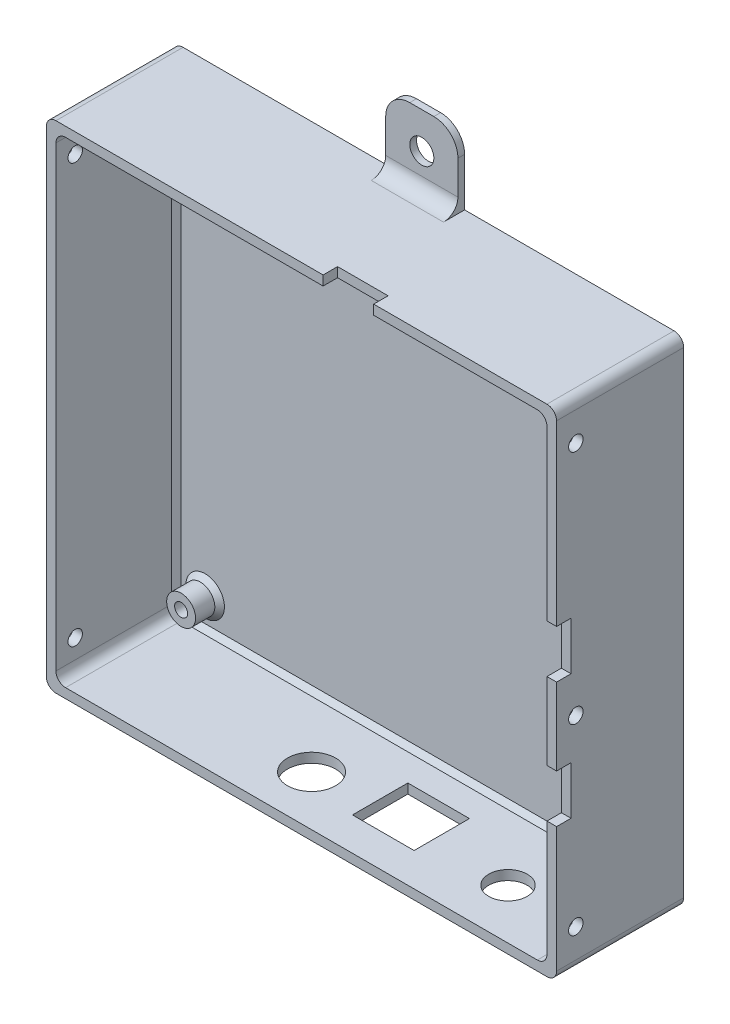
SolidWorks part; units mm, degrees
ref_plane "Спереди" through (0, 0, 0) normal (0, 0, 1) x (1, 0, 0)
ref_plane "Сверху" through (0, 0, 0) normal (0, 1, 0) x (1, 0, 0)
ref_plane "Справа" through (0, 0, 0) normal (1, 0, 0) x (0, 0, -1)
other "Configuration Table"
sketch "Эскиз1" plane through (0, 0, 0) normal (0, 0, 1) x (1, 0, 0)
  line L5 (-53, -51.5) -> (53, -51.5)
  line L6 (-53, -51.5) -> (-53, 51.5)
  line L11 (-53, 51.5) -> (53, 51.5)
  line L12 (53, -51.5) -> (53, 51.5)
  line L13 (-53, -51.5) -> (53, 51.5) construction
  line L14 (-53, 51.5) -> (53, -51.5) construction
  line L15 (-51, -49.5) -> (51, -49.5)
  line L16 (-51, -49.5) -> (-51, 49.5)
  line L17 (-51, 49.5) -> (51, 49.5)
  line L18 (51, -49.5) -> (51, 49.5)
  line L19 (-51, -49.5) -> (51, 49.5) construction
  line L20 (-51, 49.5) -> (51, -49.5) construction
  point P0 (0, 0)
  point P6 (0, 0)
  dimension "D1" = 103
  dimension "D2" = 106
  dimension "D3" = 2
  dimension "D4" = 2
extrude "Бобышка-Вытянуть1" add sketch "Эскиз1" along normal blind 25
sketch "Эскиз2" plane through (0, 0, 0) normal (0, 0, -1) x (-1, 0, 0)
  line L4 (-53, 51.5) -> (-53, -51.5)
  line L5 (-53, -51.5) -> (53, -51.5)
  line L6 (53, -51.5) -> (53, 51.5)
  line L7 (53, 51.5) -> (-53, 51.5)
  line L8 (-53, 51.5) -> (-53, -51.5)
  line L9 (-53, -51.5) -> (53, -51.5)
  line L10 (53, -51.5) -> (53, 51.5)
  line L11 (53, 51.5) -> (-53, 51.5)
  dimension "D1" = 0
extrude "Бобышка-Вытянуть2" add sketch "Эскиз2" along normal blind 1.4
sketch "Эскиз3" plane through (0, 0, 0) normal (0, 0, 1) x (1, 0, 0)
  line L0 (0, 51.5) -> (0, -51.5) construction
  line L1 (-45, -43.5) -> (45, -43.5) construction
  line L2 (-45, -43.5) -> (-45, 39.5) construction
  line L3 (-45, 39.5) -> (45, 39.5) construction
  line L4 (45, -43.5) -> (45, 39.5) construction
  line L5 (-45, -43.5) -> (45, 39.5) construction
  line L6 (-45, 39.5) -> (45, -43.5) construction
  line L7 (53, 51.5) -> (-53, 51.5) construction
  line L8 (-53, -51.5) -> (53, -51.5) construction
  circle A0 centre (-45, 39.5) radius 3
  circle A1 centre (45, 39.5) radius 3
  circle A2 centre (-45, -43.5) radius 3
  circle A3 centre (45, -43.5) radius 3
  circle A4 centre (-45, 39.5) radius 1.35
  circle A5 centre (45, 39.5) radius 1.35
  circle A6 centre (-45, -43.5) radius 1.35
  circle A7 centre (45, -43.5) radius 1.35
  point P0 (-2.3667, -6.7481)
  point P14 (0, -2)
  dimension "D3" = 6
  dimension "D4" = 2.7
  dimension "D1" = 90
  dimension "D2" = 83
  dimension "D5" = 8
extrude "Бобышка-Вытянуть3" add sketch "Эскиз3" along normal blind 5
sketch "Эскиз4" plane through (0, -51.5, 0) normal (0, -1, 0) x (1, 0, 0)
  line L0 (53, 25) -> (53, -1.4) construction
  line L1 (3.7, 18.1) -> (16.5, 18.1)
  line L2 (3.7, 18.1) -> (3.7, 6.6)
  line L3 (3.7, 6.6) -> (16.5, 6.6)
  line L4 (16.5, 18.1) -> (16.5, 6.6)
  line L5 (53, -1.4) -> (-53, -1.4) construction
  dimension "D1" = 36.5
  dimension "D2" = 12.8
  dimension "D3" = 11.5
  dimension "D4" = 8
extrude "Вырез-Вытянуть1" cut sketch "Эскиз4" against normal up to surface (101 mm away) up to face at (0, 49.5, 12.5)
fillet "Скругление1" radius 2 8 edges at (-53, -51.5, 11.8) (53, -51.5, 11.8) (53, 51.5, 11.8) (-53, 51.5, 11.8) (-51, -49.5, 12.5) (-51, 49.5, 12.5) (51, 49.5, 12.5) (51, -49.5, 12.5)
chamfer "Фаска1" distance 1 angle 45 12 edges at (-50.4142, 48.9142, 0) (0, 49.5, 0) (50.4142, 48.9142, 0) (51, 0, 0) (50.4142, -48.9142, 0) (0, -49.5, 0) (-50.4142, -48.9142, 0) (-51, 0, 0) (-48, 39.5, 0) (42, 39.5, 0) (-48, -43.5, 0) (42, -43.5, 0)
sketch "Эскиз5" plane through (0, -51.5, 0) normal (0, -1, 0) x (1, 0, 0)
  line L0 (3.7, 14.6) -> (48.1817, 14.6) construction
  line L1 (3.7, 18.1) -> (3.7, 6.6) construction
  line L2 (3.7, 14.6) -> (-48.4627, 14.6) construction
  line L3 (16.5, 6.6) -> (16.5, 18.1) construction
  line L4 (51, -1.4) -> (-51, -1.4) construction
  circle A0 centre (32.5, 14.6) radius 4
  circle A1 centre (-8.3, 14.6) radius 5
  dimension "D1" = 8
  dimension "D4" = 10
  dimension "D2" = 16
  dimension "D3" = 12
  dimension "D5" = 16
extrude "Вырез-Вытянуть2" cut sketch "Эскиз5" against normal up to surface (2 mm away) up to face at (10.1, -49.5, 12.35)
sketch "Эскиз6" plane through (53, 0, 0) normal (1, 0, 0) x (0, 0, -1)
  line L0 (-25, -49.5) -> (-25, 49.5) construction
  line L1 (-25, -13.5) -> (-22, -13.5)
  line L2 (-25, -13.5) -> (-25, -23.5)
  line L3 (-25, -23.5) -> (-22, -23.5)
  line L4 (-22, -13.5) -> (-22, -23.5)
  line L5 (1.4, -51.5) -> (-25, -51.5) construction
  line L6 (-25, 12.5) -> (-22, 12.5)
  line L7 (-25, 12.5) -> (-25, 2.5)
  line L8 (-25, 2.5) -> (-22, 2.5)
  line L9 (-22, 12.5) -> (-22, 2.5)
  dimension "D1" = 3
  dimension "D2" = 28
  dimension "D3" = 16
  dimension "D4" = 10
extrude "Вырез-Вытянуть3" cut sketch "Эскиз6" against normal up to surface (2 mm away) up to face at (51, 0, 13)
sketch "Эскиз8" plane through (53, 0, 0) normal (1, 0, 0) x (0, 0, -1)
  line L0 (-21, 51.5) -> (-21, -51.2985) construction
  line L1 (-25, 51.5) -> (1.4, 51.5) construction
  line L2 (-25, 12.5) -> (-25, 49.5) construction
  line L3 (1.4, -51.5) -> (-25, -51.5) construction
  circle A0 centre (-21, 43.5) radius 1.5
  circle A1 centre (-21, -43.5) radius 1.5
  dimension "D4" = 3
  dimension "D1" = 4
  dimension "D2" = 8
  dimension "D3" = 8
extrude "Вырез-Вытянуть4" cut sketch "Эскиз8" against normal through all
sketch "Эскиз9" plane through (53, 0, 0) normal (1, 0, 0) x (0, 0, -1)
  line L0 (-21, 43.5) -> (-21, -43.5) construction
  line L1 (1.4, -51.5) -> (-25, -51.5) construction
  circle A0 centre (-21, -5.5) radius 1.5
  dimension "D1" = 3
  dimension "D2" = 46
extrude "Вырез-Вытянуть5" cut sketch "Эскиз9" against normal up to surface (2 mm away) up to face at (51, 43.5, 22.5)
sketch "Эскиз10" plane through (0, 51.5, 0) normal (0, 1, 0) x (1, 0, 0)
  line L0 (51, -25) -> (-51, -25) construction
  line L1 (4.5, -25) -> (15, -25)
  line L2 (4.5, -25) -> (4.5, -22)
  line L3 (4.5, -22) -> (15, -22)
  line L4 (15, -25) -> (15, -22)
  line L5 (53, -22) -> (53, -25) construction
  line L6 (53, 1.4) -> (53, -25) construction
  dimension "D1" = 10.5
  dimension "D2" = 38
extrude "Вырез-Вытянуть6" cut sketch "Эскиз10" against normal up to surface (2 mm away) up to face at (0, 49.5, 13)
sketch "Эскиз11" plane through (0, 0, -1.4) normal (0, 0, -1) x (-1, 0, 0)
  line L0 (51, 51.5) -> (-51, 51.5) construction
  line L1 (-7.5, 51.5) -> (7.5, 51.5)
  line L2 (-7.5, 51.5) -> (-7.5, 61.5)
  line L3 (-2.5, 66.5) -> (2.5, 66.5)
  line L4 (7.5, 51.5) -> (7.5, 61.5)
  line L5 (0, 66.5) -> (0, 51.5) construction
  circle A0 centre (0, 59) radius 2.5
  arc A1 (2.5, 66.5) -> (7.5, 61.5) centre (2.5, 61.5) cw
  arc A2 (-7.5, 61.5) -> (-2.5, 66.5) centre (-2.5, 61.5) cw
  point P6 (0, 66.5)
  point P12 (0, 59)
  dimension "D3" = 5
  dimension "D2" = 5
  dimension "D1" = 15
  dimension "D4" = 15
extrude "Бобышка-Вытянуть4" add sketch "Эскиз11" against normal up to surface (1.4 mm away) up to face at (0, 0, 0)
fillet "Скругление2" radius 3 1 edges at (0, 51.5, 0)
